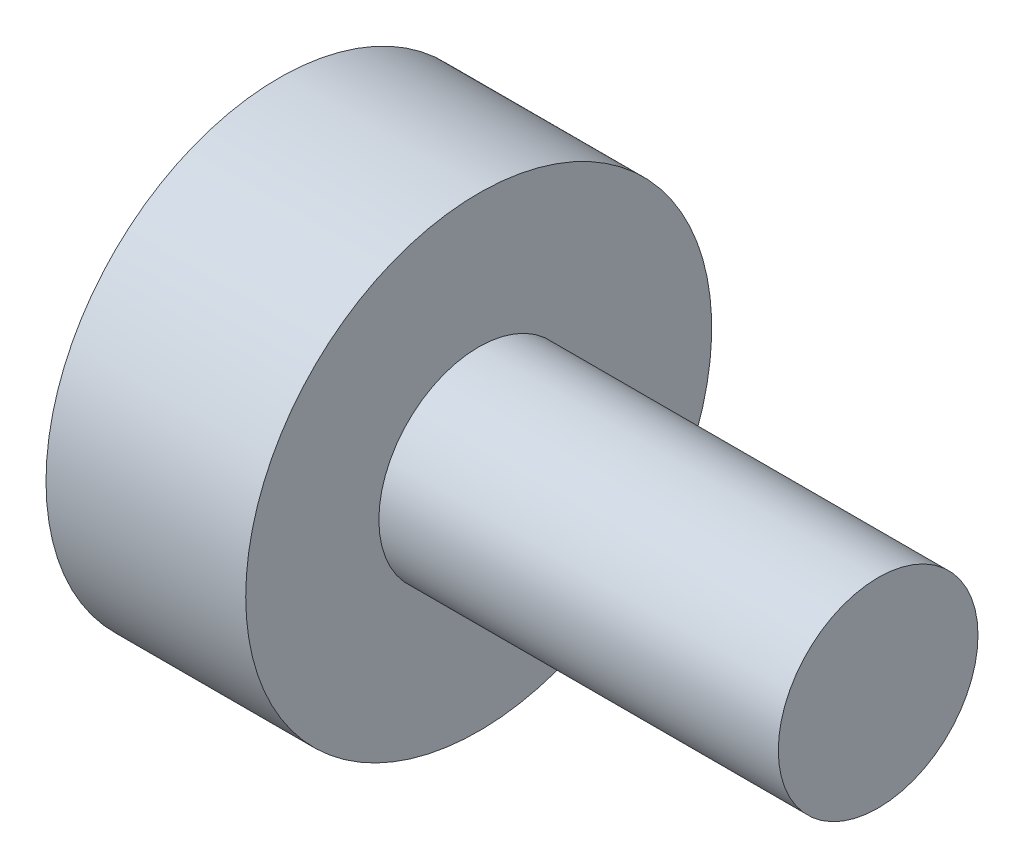
SolidWorks part; units mm, degrees
ref_plane "Спереди" through (0, 0, 0) normal (0, 0, 1) x (1, 0, 0)
ref_plane "Сверху" through (0, 0, 0) normal (0, 1, 0) x (1, 0, 0)
ref_plane "Справа" through (0, 0, 0) normal (1, 0, 0) x (0, 0, -1)
sketch "Эскиз1" plane through (0, 0, 0) normal (0, 0, 1) x (1, 0, 0)
  line L0 (0, 0) -> (100, 0)
  line L1 (0, 0) -> (0, 20)
  line L2 (0, 20) -> (10, 20)
  line L3 (10, 20) -> (10, 35)
  line L4 (10, 35) -> (40, 35)
  line L5 (40, 35) -> (40, 15)
  line L6 (40, 15) -> (100, 15)
  line L7 (100, 0) -> (100, 15)
revolve "Повернуть1" add sketch "Эскиз1" angle 360 about L0
sketch "Эскиз2" plane through (0, 0, 0) normal (1, 0, 0) x (0, 0, -1)
  circle A0 centre (0, 0) radius 5
extrude "Вырез-Вытянуть1" cut sketch "Эскиз2" along normal blind 20
sketch "Эскиз3" plane through (0, 0, 0) normal (1, 0, 0) x (0, 0, -1)
  circle A0 centre (0, 0) radius 9
extrude "Вырез-Вытянуть2" cut sketch "Эскиз3" along normal blind 5 draft 38.66
